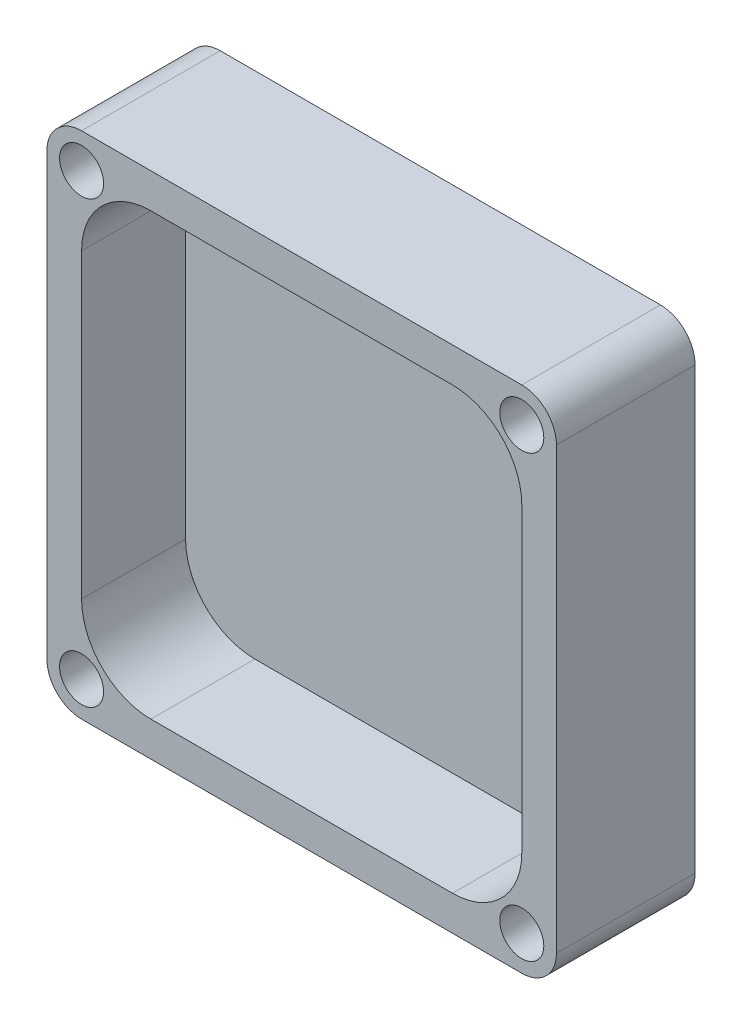
SolidWorks part; units mm, degrees
ref_plane "Front Plane" through (0, 0, 0) normal (0, 0, 1) x (1, 0, 0)
ref_plane "Top Plane" through (0, 0, 0) normal (0, 1, 0) x (1, 0, 0)
ref_plane "Right Plane" through (0, 0, 0) normal (1, 0, 0) x (0, 0, -1)
sketch "Sketch1" plane through (0, 0, 0) normal (0, 0, 1) x (1, 0, 0)
  line L0 (-73.5, -73.5) -> (-73.5, 73.5)
  line L1 (63.5, -63.5) -> (-63.5, -63.5) construction
  line L2 (63.5, -63.5) -> (63.5, 63.5) construction
  line L3 (63.5, 63.5) -> (-63.5, 63.5) construction
  line L4 (-63.5, -63.5) -> (-63.5, 63.5) construction
  line L5 (63.5, -63.5) -> (-63.5, 63.5) construction
  line L6 (63.5, 63.5) -> (-63.5, -63.5) construction
  line L7 (73.5, 73.5) -> (-73.5, 73.5)
  line L8 (73.5, -73.5) -> (73.5, 73.5)
  line L9 (73.5, -73.5) -> (-73.5, -73.5)
  circle A0 centre (-63.5, 63.5) radius 6.35
  circle A1 centre (63.5, 63.5) radius 6.35
  circle A2 centre (63.5, -63.5) radius 6.35
  circle A3 centre (-63.5, -63.5) radius 6.35
  point P0 (0, 0)
  dimension "D2" = 12.7
  dimension "D1" = 127
  dimension "D3" = 10
extrude "Boss-Extrude1" add sketch "Sketch1" along normal blind 10
sketch "Sketch2" plane through (0, 0, 10) normal (0, 0, 1) x (1, 0, 0)
  line L0 (-43.5, -63.5) -> (43.5, -63.5)
  line L1 (63.5, -43.5) -> (63.5, 43.5)
  line L2 (43.5, 63.5) -> (-43.5, 63.5)
  line L3 (-63.5, 43.5) -> (-63.5, -43.5)
  line L4 (-73.5, -73.5) -> (73.5, -73.5)
  line L5 (73.5, -73.5) -> (73.5, 73.5)
  line L6 (73.5, 73.5) -> (-73.5, 73.5)
  line L7 (-73.5, 73.5) -> (-73.5, -73.5)
  line L8 (-73.5, -73.5) -> (73.5, -73.5)
  line L9 (73.5, -73.5) -> (73.5, 73.5)
  line L10 (73.5, 73.5) -> (-73.5, 73.5)
  line L11 (-73.5, 73.5) -> (-73.5, -73.5)
  line L12 (-63.5, 63.5) -> (-63.5, -63.5) construction
  line L13 (-63.5, -63.5) -> (63.5, -63.5) construction
  line L14 (63.5, -63.5) -> (63.5, 63.5) construction
  line L15 (63.5, 63.5) -> (-63.5, 63.5) construction
  circle A0 centre (-63.5, 63.5) radius 6.35 construction
  circle A1 centre (63.5, 63.5) radius 6.35 construction
  circle A2 centre (63.5, -63.5) radius 6.35 construction
  circle A3 centre (-63.5, -63.5) radius 6.35 construction
  circle A4 centre (-63.5, -63.5) radius 6.35
  circle A5 centre (63.5, -63.5) radius 6.35
  circle A6 centre (63.5, 63.5) radius 6.35
  circle A7 centre (-63.5, 63.5) radius 6.35
  arc A8 (-63.5, -43.5) -> (-43.5, -63.5) centre (-43.5, -43.5) ccw
  arc A9 (43.5, -63.5) -> (63.5, -43.5) centre (43.5, -43.5) ccw
  arc A10 (63.5, 43.5) -> (43.5, 63.5) centre (43.5, 43.5) ccw
  arc A11 (-63.5, 43.5) -> (-43.5, 63.5) centre (-43.5, 43.5) cw
  dimension "D3" = 20
  dimension "D1" = 0
  dimension "D2" = 10
extrude "Boss-Extrude2" add sketch "Sketch2" along normal blind 30
fillet "Fillet1" radius 10 4 edges at (73.5, 73.5, 20) (73.5, -73.5, 20) (-73.5, -73.5, 20) (-73.5, 73.5, 20)
